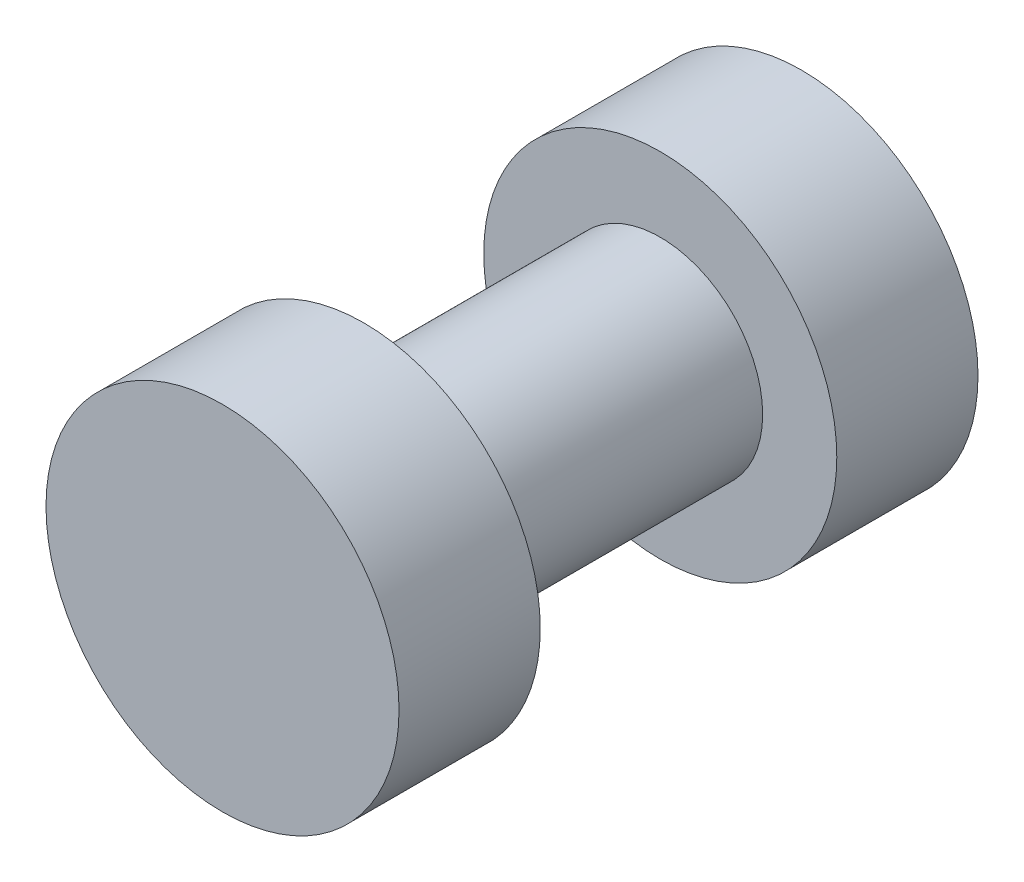
SolidWorks part; units mm, degrees
ref_plane "Front Plane" through (0, 0, 0) normal (0, 0, 1) x (1, 0, 0)
ref_plane "Top Plane" through (0, 0, 0) normal (0, 1, 0) x (1, 0, 0)
ref_plane "Right Plane" through (0, 0, 0) normal (1, 0, 0) x (0, 0, -1)
sketch "Sketch1" plane through (0, 0, 0) normal (0, 0, 1) x (1, 0, 0)
  circle A0 centre (0, 0) radius 12.5
  dimension "D1" = 25
extrude "Boss-Extrude1" add sketch "Sketch1" along normal blind 10
sketch "Sketch3" plane through (0, 0, 10) normal (0, 0, 1) x (1, 0, 0)
  circle A0 centre (0, 0) radius 7.25
  dimension "D1" = 14.5
extrude "Boss-Extrude2" add sketch "Sketch3" along normal blind 21
sketch "Sketch4" plane through (0, 0, 31) normal (0, 0, 1) x (1, 0, 0)
  circle A0 centre (0, 0) radius 12.5 construction
  circle A1 centre (0, 0) radius 12.5
extrude "Boss-Extrude3" add sketch "Sketch4" along normal blind 10
